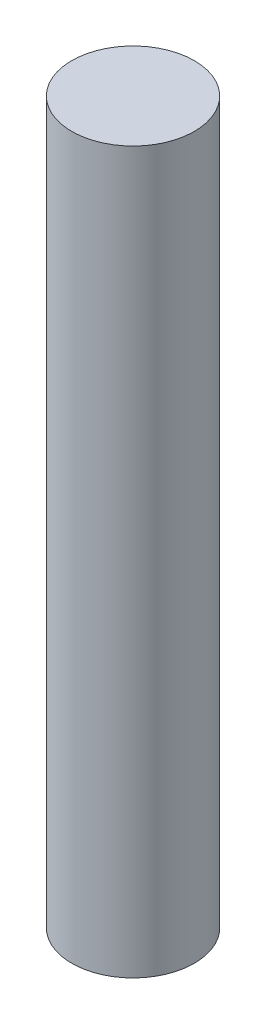
SolidWorks part; units mm, degrees
ref_plane "Front Plane" through (0, 0, 0) normal (0, 0, 1) x (1, 0, 0)
ref_plane "Top Plane" through (0, 0, 0) normal (0, 1, 0) x (1, 0, 0)
ref_plane "Right Plane" through (0, 0, 0) normal (1, 0, 0) x (0, 0, -1)
sketch "Sketch1" plane through (0, 0, 0) normal (0, 1, 0) x (1, 0, 0)
  circle A0 centre (0, 0) radius 40
  dimension "D1" = 80
extrude "Boss-Extrude1" add sketch "Sketch1" along normal blind 470
